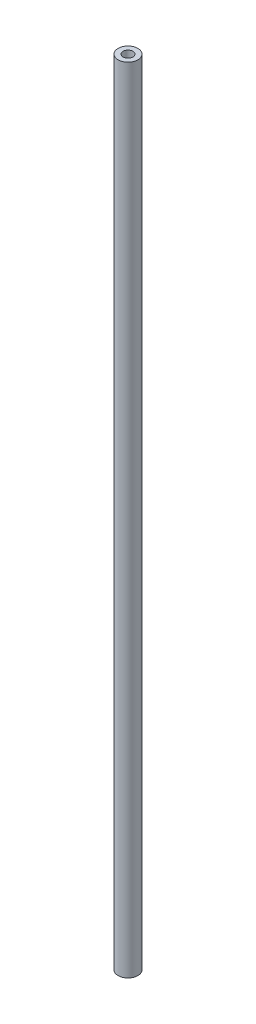
SolidWorks part; units mm, degrees
material "7075-O (SS)"
ref_plane "Front Plane" through (0, 0, 0) normal (0, 0, 1) x (1, 0, 0)
ref_plane "Top Plane" through (0, 0, 0) normal (0, 1, 0) x (1, 0, 0)
ref_plane "Right Plane" through (0, 0, 0) normal (1, 0, 0) x (0, 0, -1)
sketch "Sketch1" plane through (0, 0, 0) normal (0, 1, 0) x (1, 0, 0)
  circle A0 centre (0, 0) radius 25
  circle A1 centre (0, 0) radius 12.5
  dimension "D1" = 50
  dimension "D2" = 25
extrude "Boss-Extrude1" add sketch "Sketch1" along normal blind 2000
